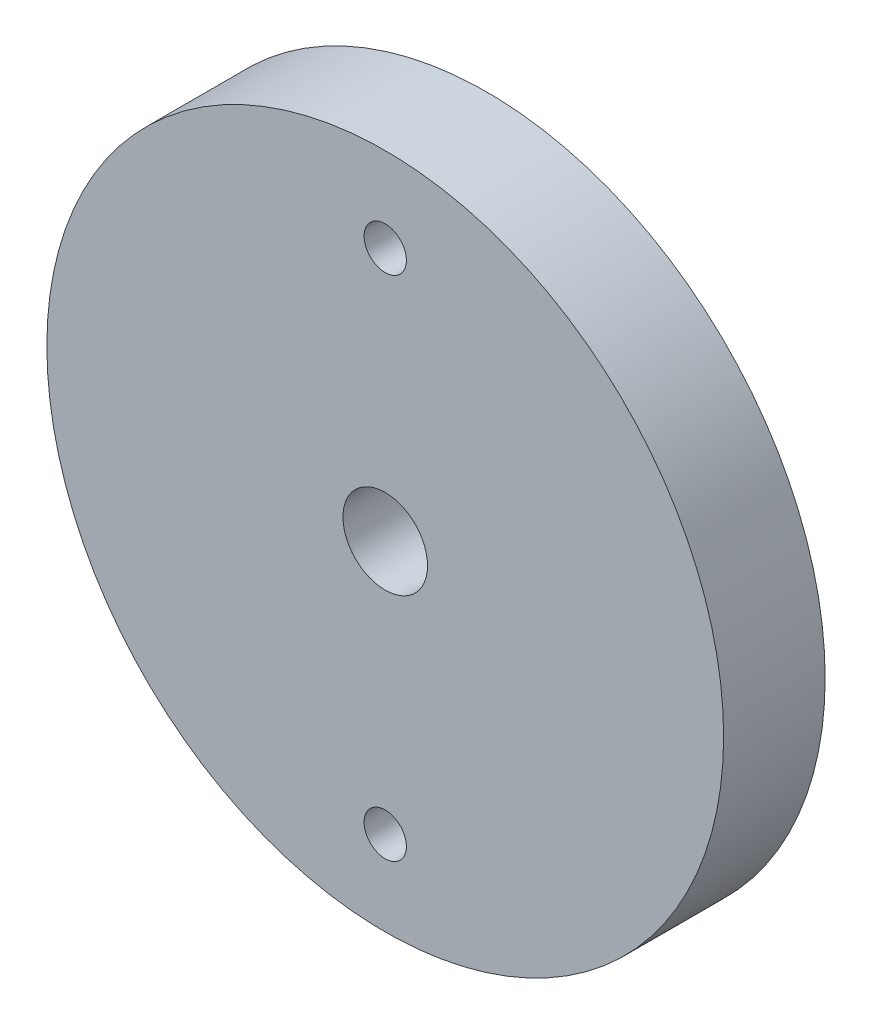
SolidWorks part; units mm, degrees
ref_plane "前视基准面" through (0, 0, 0) normal (0, 0, 1) x (1, 0, 0)
ref_plane "上视基准面" through (0, 0, 0) normal (0, 1, 0) x (1, 0, 0)
ref_plane "右视基准面" through (0, 0, 0) normal (1, 0, 0) x (0, 0, -1)
sketch "草图1" plane through (0, 0, 0) normal (0, 0, 1) x (1, 0, 0)
  circle A0 centre (0, 0) radius 40
  dimension "D1" = 80
extrude "凸台-拉伸1" add sketch "草图1" along normal blind 12
sketch "草图2" plane through (0, 0, 12) normal (0, 0, 1) x (1, 0, 0)
  circle A0 centre (0, 0) radius 5
  circle A1 centre (0, 30) radius 2.5
  circle A2 centre (0, -30) radius 2.5
  dimension "D1" = 10
  dimension "D2" = 5
  dimension "D4" = 5
  dimension "D3" = 30
  dimension "D5" = 30
extrude "切除-拉伸1" cut sketch "草图2" against normal blind 10
sketch "草图3" plane through (0, 0, 0) normal (0, 0, -1) x (-1, 0, 0)
  circle A0 centre (0, -30) radius 4.75
  circle A1 centre (0, 30) radius 4.75
  dimension "D1" = 9.5
  dimension "D2" = 9.5
extrude "切除-拉伸2" cut sketch "草图3" against normal blind 5
